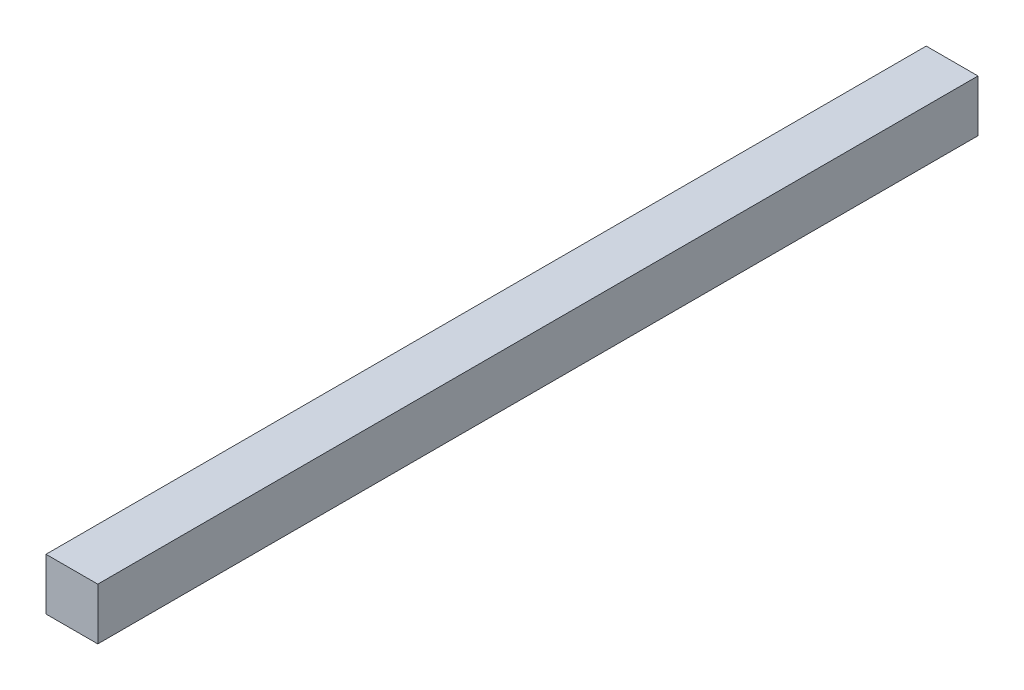
SolidWorks part; units mm, degrees
ref_plane "前基準面" through (0, 0, 0) normal (0, 0, 1) x (1, 0, 0)
ref_plane "上基準面" through (0, 0, 0) normal (0, 1, 0) x (1, 0, 0)
ref_plane "右基準面" through (0, 0, 0) normal (1, 0, 0) x (0, 0, -1)
sketch "草圖1" plane through (0, 0, 0) normal (0, 0, 1) x (1, 0, 0)
  line L1 (-10, 10) -> (10, 10)
  line L2 (-10, 10) -> (-10, -10)
  line L3 (-10, -10) -> (10, -10)
  line L4 (10, 10) -> (10, -10)
  point P4 (0, 10)
  point P6 (10, 0)
  dimension "D1" = 20
  dimension "D2" = 20
extrude "填料-伸長1" add sketch "草圖1" along normal blind 340
sketch "草圖2" plane through (0, 10, 0) normal (0, 1, 0) x (1, 0, 0)
  line L0 (-10, -170) -> (10, -170) construction
  line L1 (-10, -340) -> (-10, 0) construction
  line L2 (10, -340) -> (10, 0) construction
  line L3 (-10, -100) -> (10, -100) construction
  line L4 (-10, -240) -> (10, -240) construction
  dimension "D1" = 70
  dimension "D2" = 70
sketch "草圖3" plane through (0, 10, 0) normal (0, 1, 0) x (1, 0, 0)
  line L0 (0, 0) -> (0, -340) construction
  line L1 (10, -340) -> (-10, -340) construction
